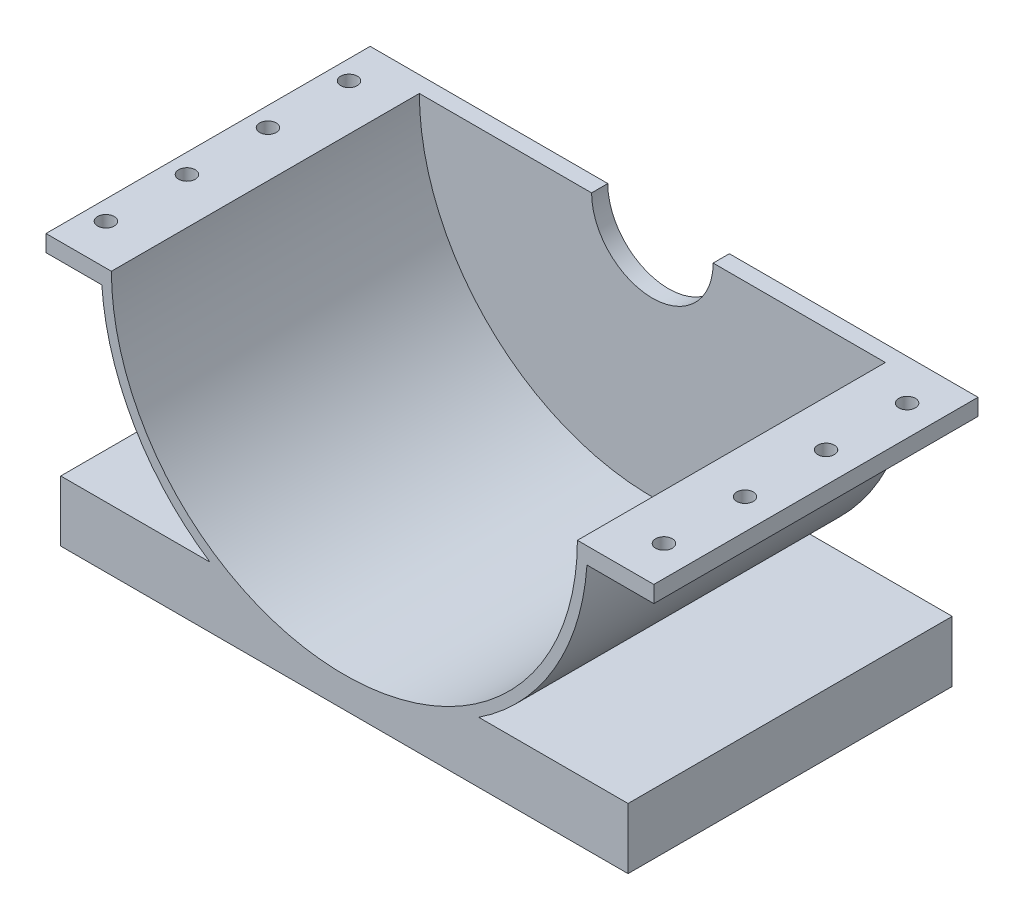
SolidWorks part; units mm, degrees
ref_plane "Front Plane" through (0, 0, 0) normal (0, 0, 1) x (1, 0, 0)
ref_plane "Top Plane" through (0, 0, 0) normal (0, 1, 0) x (1, 0, 0)
ref_plane "Right Plane" through (0, 0, 0) normal (1, 0, 0) x (0, 0, -1)
sketch "Sketch2" plane through (0, 0, 0) normal (0, 0, 1) x (1, 0, 0)
  line L0 (-187.0428, 0) -> (193.9572, 0)
  line L1 (-187.0428, 0) -> (-187.0428, -10.414)
  line L2 (-177.8, -127) -> (-84.2423, -127)
  line L3 (-177.8, -127) -> (-177.8, -165.1)
  line L4 (-177.8, -165.1) -> (177.8, -165.1)
  line L5 (177.8, -127) -> (177.8, -165.1)
  line L6 (-187.0428, -10.414) -> (-152.0438, -10.414)
  line L7 (193.9572, -10.414) -> (193.9572, 0)
  line L8 (152.0438, -10.414) -> (193.9572, -10.414)
  line L9 (84.2423, -127) -> (177.8, -127)
  arc A0 (-152.0438, -10.414) -> (-84.2423, -127) centre (0, 0) ccw
  arc A1 (84.2423, -127) -> (152.0438, -10.414) centre (0, 0) ccw
  point P1 (0, -165.1)
  dimension "D2" = 152.4
  dimension "D1" = 381
  dimension "D3" = 165.1
  dimension "D4" = 38.1
  dimension "D5" = 355.6
  dimension "D6" = 10.414
extrude "Boss-Extrude1" add sketch "Sketch2" along normal mid plane 203.2
sketch "Sketch3" plane through (0, 0, 101.6) normal (0, 0, 1) x (1, 0, 0)
  line L0 (-146.05, 0) -> (146.05, 0)
  arc A0 (-146.05, 0) -> (146.05, 0) centre (0, 0) ccw
  arc A1 (84.2423, -127) -> (152.0438, -10.414) centre (0, 0) ccw construction
  dimension "D1" = 146.05
extrude "Cut-Extrude1" cut sketch "Sketch3" against normal blind 193.04
sketch "Sketch4" plane through (0, 0, -91.44) normal (0, 0, 1) x (1, 0, 0)
  line L0 (-38.1, 0) -> (38.1, 0)
  arc A0 (-38.1, 0) -> (38.1, 0) centre (0, 0) ccw
  dimension "D1" = 38.1
extrude "Cut-Extrude2" cut sketch "Sketch4" against normal through all
sketch "Sketch5" plane through (0, 0, 0) normal (0, 1, 0) x (1, 0, 0)
  line L0 (193.9572, 101.6) -> (38.1, 101.6) construction
  line L1 (193.9572, -101.6) -> (146.05, -101.6) construction
  line L2 (193.9572, -101.6) -> (193.9572, 101.6) construction
  circle A0 centre (174.9072, -76.2) radius 5.207
  circle A1 centre (174.9072, -25.4) radius 5.207
  circle A2 centre (174.9072, 25.4) radius 5.207
  circle A3 centre (174.9072, 76.2) radius 5.207
  dimension "D5" = 10.414
  dimension "D1" = 25.4
  dimension "D2" = 25.4
  dimension "D3" = 50.8
  dimension "D4" = 50.8
  dimension "D6" = 19.05
extrude "Cut-Extrude4" cut sketch "Sketch5" against normal blind 82.042
mirror "Mirror1" about plane through (0, 0, 0) normal (1, 0, 0) of "Cut-Extrude4"
